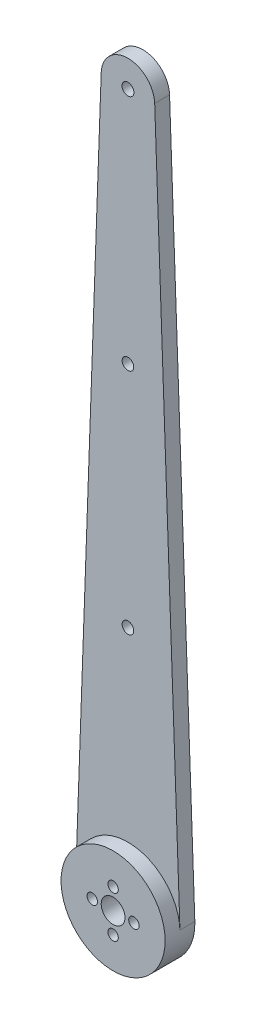
SolidWorks part; units mm, degrees
ref_plane "Front Plane" through (0, 0, 0) normal (0, 0, 1) x (1, 0, 0)
ref_plane "Top Plane" through (0, 0, 0) normal (0, 1, 0) x (1, 0, 0)
ref_plane "Right Plane" through (0, 0, 0) normal (1, 0, 0) x (0, 0, -1)
sketch "Sketch7" plane through (0, 0, 0) normal (0, 0, 1) x (1, 0, 0)
  line L0 (8.9942, 237.1231) -> (17.4887, 0.6282)
  line L1 (-8.9942, 237.1231) -> (-17.4887, 0.6282)
  line L4 (0, 236.8) -> (0, 0) construction
  circle A8 centre (0, 0) radius 4
  arc A11 (-17.4887, 0.6282) -> (17.4887, 0.6282) centre (0, 0) ccw
  circle A12 centre (0, 236.8) radius 2
  arc A13 (8.9942, 237.1231) -> (-8.9942, 237.1231) centre (0, 236.8) ccw
  dimension "D1" = 8
  dimension "D2" = 35
  dimension "D3" = 4
  dimension "D4" = 18
  dimension "D5" = 236.8
extrude "Boss-Extrude1" add sketch "Sketch7" against normal blind 5
sketch "草图2" plane through (0, 0, 0) normal (0, 0, 1) x (1, 0, 0)
  line L0 (0, 236.8) -> (0, 0) construction
  point P4 (0, 80)
  point P5 (0, 156.8)
  dimension "D1" = 80
  dimension "D2" = 80
hole_wizard "M3.5 间隙孔1" positions "3D草图2" profile "草图3" hole size "M3.5" standard "ISO"
sketch3d "3D草图2"
  point P0 (0, 156.8, 0)
  point P3 (0, 80, 0)
sketch "草图3" plane through (0, 156.8, 0) normal (1, 0, 0) x (0, -1, 0)
  line L0 (0, 0) -> (0, 11.1717)
  line L1 (0, 11.1717) -> (1.95, 10)
  line L2 (1.95, 10) -> (1.95, 0)
  line L5 (1.95, 0) -> (0, 0)
  line L10 (0, 11.1717) -> (-1.95, 10) construction
  line L11 (0, -6.35) -> (0, 107.95) construction
  dimension "孔直径" = 3.9
  dimension "孔深度" = 10
  dimension "导头角度" = 118
sketch "草图4" plane through (0, 0, 0) normal (0, 0, 1) x (1, 0, 0)
  line L0 (-7, 0) -> (7, 0) construction
  line L1 (0, -7) -> (0, 7) construction
  circle A0 centre (7, 0) radius 1.75
  circle A1 centre (0, 7) radius 1.75
  circle A2 centre (0, -7) radius 1.75
  circle A3 centre (-7, 0) radius 1.75
  point P8 (0, 0)
  point P9 (0, 0)
  dimension "D1" = 3.5
  dimension "D2" = 3.5
  dimension "D3" = 3.5
  dimension "D4" = 3.5
  dimension "D5" = 14
  dimension "D6" = 14
extrude "切除-拉伸1" cut sketch "草图4" against normal blind 10
sketch "草图5" plane through (0, 0, 0) normal (0, 0, 1) x (1, 0, 0)
  circle A0 centre (0, 0) radius 17.5
  circle A1 centre (7, 0) radius 1.75 construction
  circle A2 centre (0, -7) radius 1.75 construction
  circle A3 centre (0, 0) radius 4 construction
  circle A4 centre (-7, 0) radius 1.75 construction
  circle A5 centre (0, 7) radius 1.75 construction
  circle A6 centre (7, 0) radius 1.75
  circle A7 centre (0, -7) radius 1.75
  circle A8 centre (0, 0) radius 4
  circle A9 centre (-7, 0) radius 1.75
  circle A10 centre (0, 7) radius 1.75
extrude "凸台-拉伸1" add sketch "草图5" along normal blind 5
